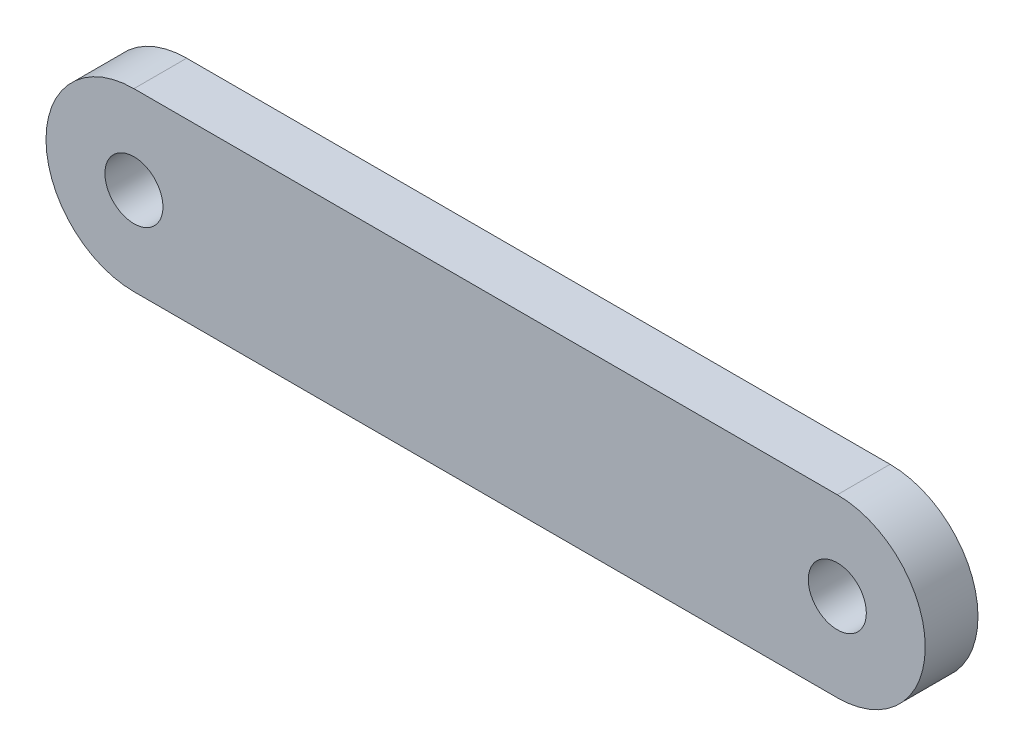
SolidWorks part; units mm, degrees
ref_plane "前视基准面" through (0, 0, 0) normal (0, 0, 1) x (1, 0, 0)
ref_plane "上视基准面" through (0, 0, 0) normal (0, 1, 0) x (1, 0, 0)
ref_plane "右视基准面" through (0, 0, 0) normal (1, 0, 0) x (0, 0, -1)
sketch "草图1" plane through (0, 0, 0) normal (0, 0, 1) x (1, 0, 0)
  line L0 (0, 0) -> (40, 0)
  line L1 (0, -10) -> (40, -10)
  arc A0 (0, 0) -> (0, -10) centre (0, -5) ccw
  arc A1 (40, 0) -> (40, -10) centre (40, -5) cw
  circle A2 centre (0, -5) radius 1.65
  circle A3 centre (40, -5) radius 1.65
  dimension "D2" = 40
  dimension "D1" = 10
extrude "凸台-拉伸1" add sketch "草图1" along normal blind 3
